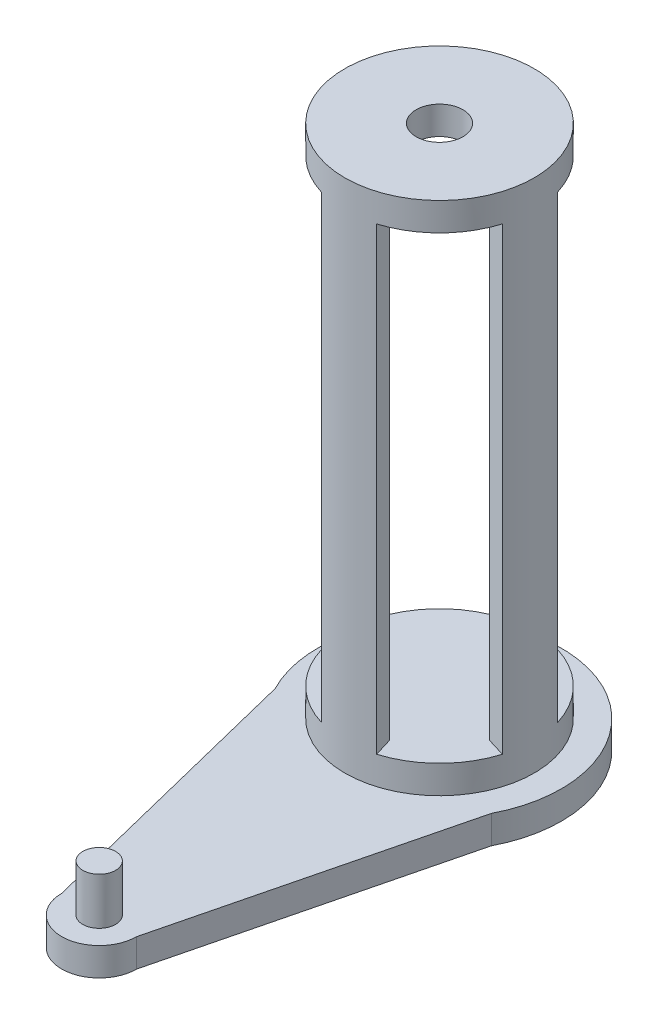
SolidWorks part; units mm, degrees
ref_plane "Front Plane" through (0, 0, 0) normal (0, 0, 1) x (1, 0, 0)
ref_plane "Top Plane" through (0, 0, 0) normal (0, 1, 0) x (1, 0, 0)
ref_plane "Right Plane" through (0, 0, 0) normal (1, 0, 0) x (0, 0, -1)
sketch "Sketch1" plane through (0, 0, 0) normal (0, 1, 0) x (1, 0, 0)
  circle A0 centre (0, 0) radius 10.1
  dimension "D1" = 20.2
extrude "Boss-Extrude1" add sketch "Sketch1" along normal blind 3
sketch "Sketch2" plane through (0, 3, 0) normal (0, 1, 0) x (1, 0, 0)
  line L0 (0, 0) -> (-2.953, 9.6587) construction
  line L1 (0, 0) -> (2.953, 9.6587) construction
  line L2 (0, 0) -> (0, 10.1) construction
  line L3 (-2.953, 9.6587) -> (-2.339, 7.6504)
  line L4 (2.953, 9.6587) -> (2.339, 7.6504)
  line L5 (9.6587, 2.953) -> (7.6504, 2.339)
  line L6 (9.6587, -2.953) -> (7.6504, -2.339)
  line L7 (2.953, -9.6587) -> (2.339, -7.6504)
  line L8 (-2.953, -9.6587) -> (-2.339, -7.6504)
  line L9 (-9.6587, -2.953) -> (-7.6504, -2.339)
  line L10 (-9.6587, 2.953) -> (-7.6504, 2.339)
  arc A0 (2.339, 7.6504) -> (-2.339, 7.6504) centre (0, 0) ccw
  arc A1 (2.953, 9.6587) -> (-2.953, 9.6587) centre (0, 0) ccw
  arc A2 (9.6587, -2.953) -> (9.6587, 2.953) centre (0, 0) ccw
  arc A3 (7.6504, -2.339) -> (7.6504, 2.339) centre (0, 0) ccw
  arc A4 (-2.953, -9.6587) -> (2.953, -9.6587) centre (0, 0) ccw
  arc A5 (-2.339, -7.6504) -> (2.339, -7.6504) centre (0, 0) ccw
  arc A6 (-9.6587, 2.953) -> (-9.6587, -2.953) centre (0, 0) ccw
  arc A7 (-7.6504, 2.339) -> (-7.6504, -2.339) centre (0, 0) ccw
  point P22 (0, 0)
  dimension "D1" = 20.2
  dimension "D2" = 16
  dimension "D3" = 17
  dimension "D4" = 17
  dimension "D5" = 4
extrude "Boss-Extrude2" add sketch "Sketch2" along normal blind 49
sketch "Sketch3" plane through (0, 52, 0) normal (0, 1, 0) x (1, 0, 0)
  circle A0 centre (0, 0) radius 10.1
  circle A1 centre (0, 0) radius 2.5
  dimension "D1" = 20.2
  dimension "D2" = 5
extrude "Boss-Extrude3" add sketch "Sketch3" along normal blind 3
sketch "Sketch4" plane through (0, 0, 0) normal (0, -1, 0) x (1, 0, 0)
  line L0 (0, 0) -> (0, 32.8) construction
  line L1 (-11.5326, 5.9998) -> (-4, 36.31)
  line L2 (11.5326, 5.9998) -> (4, 36.31)
  line L3 (0, 34.8) -> (0, 36.31) construction
  arc A0 (-11.5326, 5.9998) -> (11.5326, 5.9998) centre (0, 0) ccw
  arc A1 (4, 36.31) -> (-4, 36.31) centre (0, 36.31) ccw
  dimension "D1" = 26
  dimension "D2" = 8
  dimension "D3" = 36.31
extrude "Boss-Extrude6" add sketch "Sketch4" along normal blind 3
sketch "Sketch5" plane through (0, 0, 0) normal (0, 1, 0) x (1, 0, 0)
  line L0 (0, 0) -> (0, -36.31) construction
  circle A0 centre (0, -36.31) radius 1.75
  dimension "D1" = 36.31
  dimension "D2" = 3.5
extrude "Boss-Extrude7" add sketch "Sketch5" along normal blind 5
